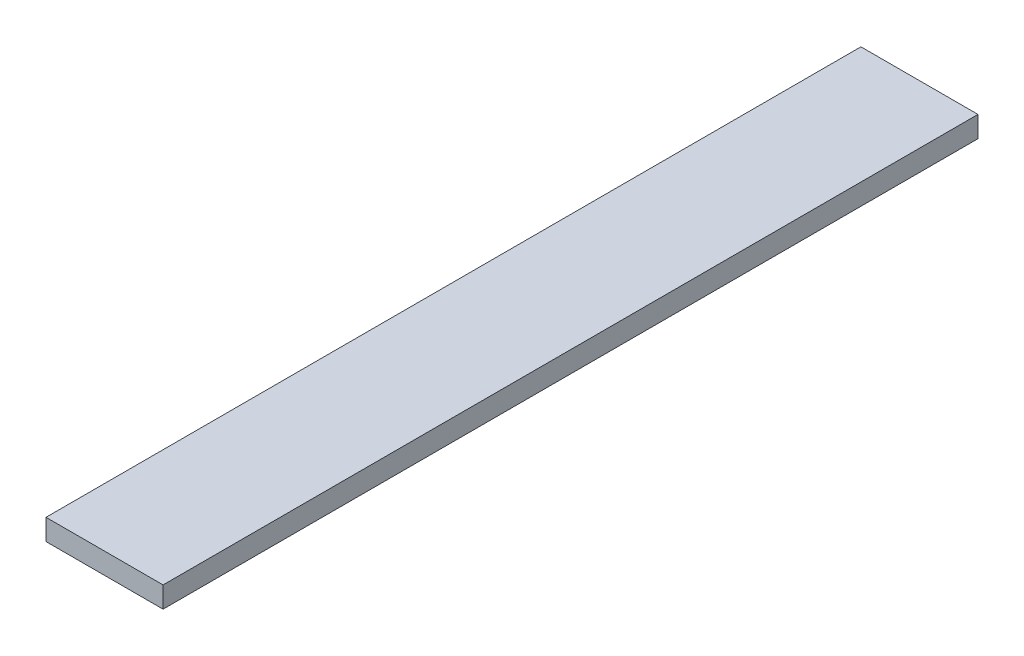
SolidWorks part; units mm, degrees
ref_plane "Front Plane" through (0, 0, 0) normal (0, 0, 1) x (1, 0, 0)
ref_plane "Top Plane" through (0, 0, 0) normal (0, 1, 0) x (1, 0, 0)
ref_plane "Right Plane" through (0, 0, 0) normal (1, 0, 0) x (0, 0, -1)
sketch "Sketch1" plane through (0, 0, 0) normal (0, 1, 0) x (1, 0, 0)
  line L1 (-50.8, -353.568) -> (50.8, -353.568)
  line L2 (-50.8, -353.568) -> (-50.8, 353.568)
  line L3 (-50.8, 353.568) -> (50.8, 353.568)
  line L4 (50.8, -353.568) -> (50.8, 353.568)
  line L5 (-50.8, -353.568) -> (50.8, 353.568) construction
  line L6 (-50.8, 353.568) -> (50.8, -353.568) construction
  point P0 (0, 0)
  dimension "D1" = 707.136
  dimension "D2" = 101.6
extrude "Boss-Extrude1" add sketch "Sketch1" along normal blind 18.2562
